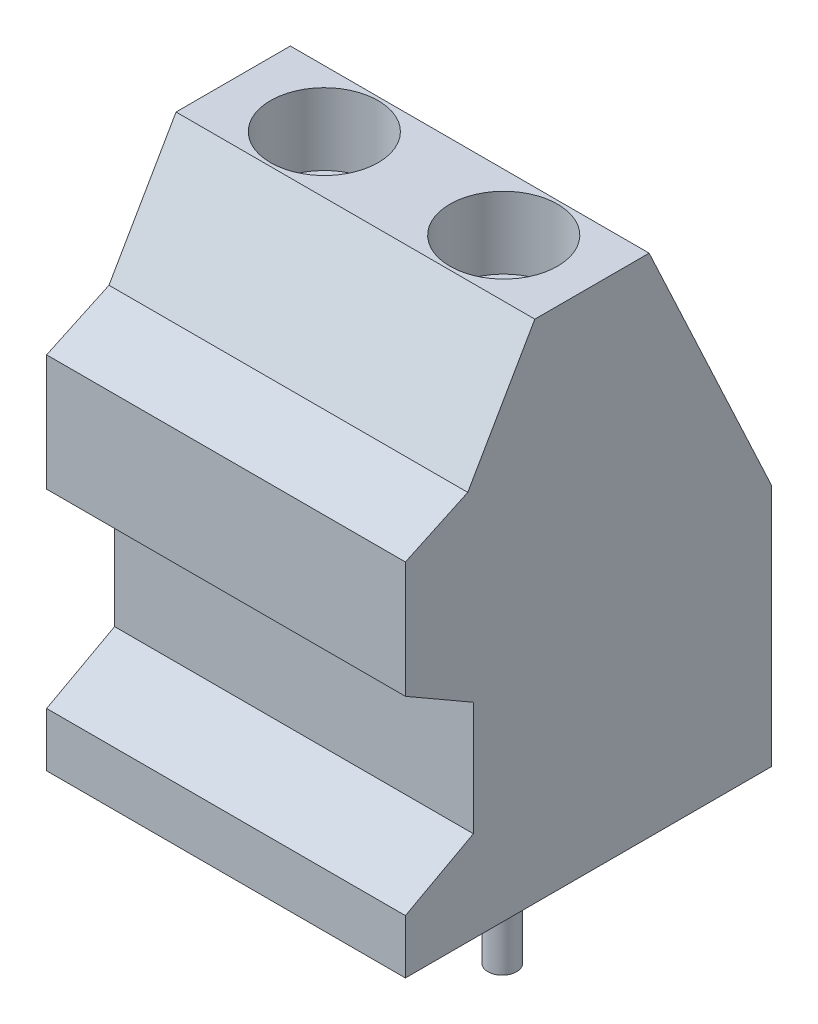
SolidWorks part; units mm, degrees
ref_plane "前视基准面" through (0, 0, 0) normal (0, 0, 1) x (1, 0, 0)
ref_plane "上视基准面" through (0, 0, 0) normal (0, 1, 0) x (1, 0, 0)
ref_plane "右视基准面" through (0, 0, 0) normal (1, 0, 0) x (0, 0, -1)
sketch "草图1" plane through (0, 0, 0) normal (1, 0, 0) x (0, 0, -1)
  line L0 (0, 30.1837) -> (0, -33.3778) construction
  line L1 (0, 0) -> (5, 0)
  line L2 (5, 0) -> (5, 6.7989)
  line L3 (5, 6.7989) -> (1.5929, 14.1)
  line L4 (1.5929, 14.1) -> (-1.5929, 14.1)
  line L5 (-1.5929, 14.1) -> (-3.4622, 10.8528)
  line L6 (-3.4622, 10.8528) -> (-5.2, 10.0418)
  line L7 (-5.2, 10.0418) -> (-5.2, 6.7989)
  line L8 (-5.2, 6.7989) -> (-3.3058, 5.7085)
  line L9 (-3.3058, 5.7085) -> (-3.3058, 2.5346)
  line L10 (-3.3058, 2.5346) -> (-5.2, 1.5061)
  line L11 (-5.2, 1.5061) -> (-5.2, 0)
  line L12 (-5.2, 0) -> (0, 0)
  point P7 (0, 0)
  dimension "D1" = 5
  dimension "D2" = 14.1
  dimension "D3" = 10.2
extrude "凸台-拉伸1" add sketch "草图1" along normal blind 10
sketch "草图2" plane through (0, 14.1, 0) normal (0, 1, 0) x (1, 0, 0)
  line L0 (-3.4571, 0) -> (11.4473, 0) construction
  line L1 (0, 1.5929) -> (0, -1.5929) construction
  circle A0 centre (2.54, 0) radius 1.5
  circle A1 centre (7.54, 0) radius 1.5
  dimension "D3" = 3
  dimension "D1" = 2.54
  dimension "D2" = 2
extrude "切除-拉伸1" cut sketch "草图2" against normal blind 2
sketch "草图3" plane through (0, 0, 0) normal (0, -1, 0) x (1, 0, 0)
  line L0 (-3.0899, 0) -> (13.0228, 0) construction
  line L1 (0, 5.2) -> (0, -5) construction
  circle A0 centre (2.5, 0) radius 0.4
  circle A1 centre (7.5, 0) radius 0.4
  dimension "D1" = 0.8
  dimension "D2" = 2.5
  dimension "D3" = 2
extrude "凸台-拉伸2" add sketch "草图3" along normal blind 3.5
